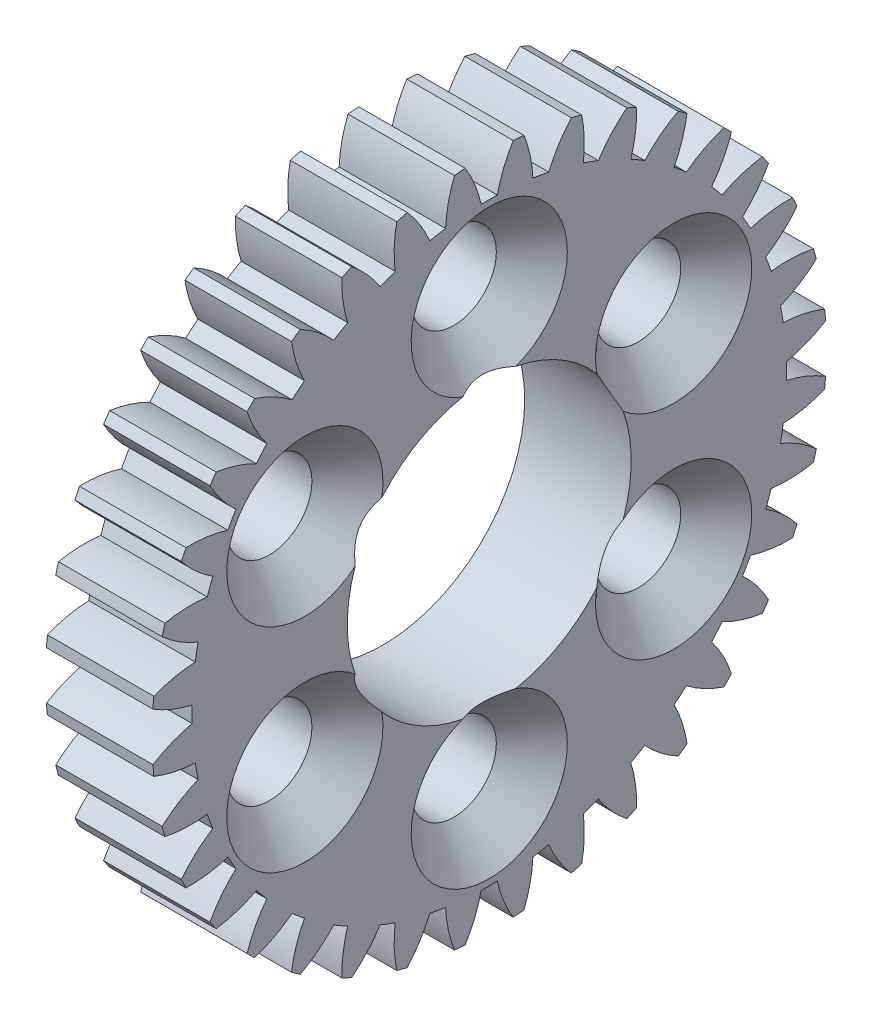
SolidWorks part; units mm, degrees
material "Náilon 101"
ref_plane "Plane1" through (0, 0, 0) normal (0, 0, 1) x (1, 0, 0)
ref_plane "Plane2" through (0, 0, 0) normal (0, 1, 0) x (1, 0, 0)
ref_plane "Plane3" through (0, 0, 0) normal (1, 0, 0) x (0, 0, -1)
sketch "HoldingSke" plane through (0, 0, 0) normal (0, 1, 0) x (1, 0, 0)
  line L0 (0, 0) -> (1.618, -1.1756)
  line L1 (-15, 0) -> (100, 0) construction
  line L2 (0, 0) -> (-2.1039, 2.3779)
  line L3 (0, 0) -> (-11.863, 4.5341)
  line L4 (0, 0) -> (6.9867, 5.0761)
  line L5 (0, 0) -> (-46.8476, -17.4728)
  line L6 (0, 0) -> (-2.4869, -1.6779)
  line L7 (-2.1039, 2.3779) -> (8.6586, 51.2059)
  line L8 (-76.2, 54.61) -> (-74.8, 54.61)
  line L9 (-71.009, 38.7566) -> (-53.1078, 45.2721)
  line L10 (-76.2, 71.12) -> (104.1128, 71.12)
  line L11 (0, 0) -> (-3, 0)
  line L12 (-76.2, 101.6) -> (-76.181, 101.6)
  line L13 (24.9733, 27.94) -> (52.9518, 28.4284)
  line L14 (24.9733, 27.94) -> (24.9743, 27.94)
  line L15 (24.9733, 27.94) -> (100.4006, 29.5858)
  line L16 (-63.627, -0.5) -> (-12.827, -0.5)
  circle A0 centre (0, 0) radius 4
  circle A1 centre (0, 0) radius 8.374
  circle A2 centre (0, 0) radius 37.5
  circle A3 centre (0, 0) radius 4
  dimension "MHD" = 16.748
  dimension "Hub_dia" = 75
  dimension "Bore" = 8
  dimension "MBD" = 8
  dimension "Num_teeth" = 36
  dimension "Pitch" = 2
  dimension "Overall_len" = 50
  dimension "Show_teeth" = 36
  dimension "Thickness" = 3
  dimension "OAL" = 50.0001
  dimension "T_dim" = 1.4
  dimension "Ap" = 20
  dimension "H" = 19.05
  dimension "Pitch_radius" = 180.3128
  dimension "Width" = 3
  dimension "Backlash" = 0.019
  dimension "Addendum_fac" = 1
  dimension "Dedendum_fac" = 1.25
  dimension "Clearance_fac" = 0.25
  dimension "Dedendum_add" = 0.001
  dimension "Module" = 0.5
sketch "BasProSke" plane through (0, 0, 0) normal (0, 1, 0) x (1, 0, 0)
  line L0 (-10, 0) -> (60, 0) construction
  line L1 (0, 0) -> (0, 9.5)
  line L2 (0, 0) -> (3, 0)
  line L3 (3, 0) -> (3, 9.5)
  line L4 (3, 9.5) -> (0, 9.5)
  dimension "Thickness" = 3
  dimension "Diameter" = 19
revolve "Base-Revolve" add sketch "BasProSke" angle 360 about L0
sketch "TooCutSke" plane through (0, 0, 0) normal (1, 0, 0) x (0, 0, -1)
  line L1 (0, 0) -> (0, 107) construction
  line L2 (0, 0) -> (-0.4258, 8.9899) construction
  line L3 (0, 0) -> (-1.5676, 17.9172) construction
  line L4 (-0.4258, 8.9899) -> (-0.7838, 8.9586) construction
  arc A0 (0.2272, 8.3709) -> (-0.2272, 8.3709) centre (0, 0) ccw
  arc A1 (0.6921, 9.5002) -> (-0.6921, 9.5002) centre (0, 0) ccw
  circle A2 centre (0, 0) radius 9 construction
  circle A3 centre (0, 0) radius 8.4572 construction
  arc A4 (-0.2272, 8.3709) -> (-0.6921, 9.5002) centre (-3.7404, 7.5851) ccw
  arc A5 (0.6921, 9.5002) -> (0.2272, 8.3709) centre (3.7404, 7.5851) ccw
  dimension "Root_dia" = 16.748
  dimension "Overcut_dia" = 19.0508
  dimension "Pitch_dia" = 18
  dimension "Base_dia" = 16.9145
  dimension "Flank_rad" = 3.6
  dimension "Half_ang" = 5
  dimension "Half_CT" = 0.3593
extrude "ToothCut" cut sketch "TooCutSke" along normal through all
fillet "Breaks" [suppressed] radius 0.01
fillet "RootFillets" [suppressed] radius 0.126
pattern_circular "TeethCuts" count 36 every 10 about axis through (-10, 0, 0) along (1, 0, 0) of "ToothCut", "RootFillets", "Breaks"
sketch "HubNeaOneSke" plane through (0, 0, 0) normal (-1, 0, 0) x (0, 0, 1)
  circle A0 centre (0, 0) radius 8.374
  dimension "Diameter" = 16.748
extrude "HubNearOne" [suppressed] add sketch "HubNeaOneSke" along normal blind 47.0001
sketch "HubNeaBotSke" plane through (0, 0, 0) normal (-1, 0, 0) x (0, 0, 1)
  circle A0 centre (0, 0) radius 8.374
  dimension "Diameter" = 16.748
extrude "HubNearBoth" [suppressed] add sketch "HubNeaBotSke" along normal blind 23.5
ref_plane "FarPln" through (3, 0, 0) normal (1, 0, 0) x (0, 0, -1)
sketch "HubFarSke" plane through (3, 0, 0) normal (1, 0, 0) x (0, 0, -1)
  circle A0 centre (0, 0) radius 8.374
  dimension "Diameter" = 16.748
extrude "HubFar" [suppressed] add sketch "HubFarSke" along normal blind 23.5
sketch "BorSke" plane through (0, 0, 0) normal (1, 0, 0) x (0, 0, -1)
  circle A0 centre (0, 0) radius 4
  dimension "Diameter" = 8
extrude "Bore" cut sketch "BorSke" along normal mid plane 100.0001
sketch "KeySke" plane through (0, 0, 0) normal (1, 0, 0) x (0, 0, -1)
  line L0 (-1.5, 0) -> (-1.5, 5.4)
  line L1 (-1.5, 5.4) -> (1.5, 5.4)
  line L2 (1.5, 5.4) -> (1.5, 0)
  line L3 (0, 0) -> (0, 34) construction
  line L4 (-1.5, 0) -> (1.5, 0)
  dimension "Width" = 3
  dimension "Offset" = 5.4
extrude "Keyway" [suppressed] cut sketch "KeySke" along normal mid plane 100.0001
pattern_circular "Keyway2" [suppressed] count 2 every 90 about axis through (-10, 0, 0) along (1, 0, 0)
sketch "Esboço1" plane through (3, 0, 0) normal (1, 0, 0) x (0, 0, -1)
  circle A0 centre (0, 0) radius 6 construction
  point P3 (0, 6)
  dimension "D1" = 12
hole_wizard "Escareado para parafuso com cabeça escareada chata de M21" positions "3DSketch2" profile "Esboço2" countersink size "M2" standard "ISO"
sketch3d "3DSketch2"
  point P0 (3, 6, 0)
sketch "Esboço2" plane through (3, 6, 0) normal (0, 1, 0) x (0, 0, -1)
  line L0 (0, 0) -> (0, 3.721)
  line L1 (0, 3.721) -> (1.2, 3)
  line L2 (1.2, 3) -> (1.2, 1)
  line L3 (1.2, 1) -> (2.2, 0)
  line L5 (2.2, 0) -> (0, 0)
  line L6 (-1.2, 1) -> (-2.2, 0) construction
  line L10 (0, 3.721) -> (-1.2, 3) construction
  line L11 (0, -6.35) -> (0, 107.95) construction
  dimension "Hole Dia." = 2.4
  dimension "Hole Depth" = 3
  dimension "Near C'Sink Dia." = 4.4
  dimension "Near C'Sink Angle" = 90
  dimension "Drill Angle" = 118
pattern_circular "PadrãoCircular1" count 6 over 360 about axis through (0, 0, 0) along (1, 0, 0) of "Escareado para parafuso com cabeça escareada chata de M21"
sketch "Esboço3" plane through (3, 0, 0) normal (1, 0, 0) x (0, 0, -1)
  line L0 (0, 0) -> (4, 0) construction
  line L1 (0, 0) -> (-4, 0) construction
  arc A0 (-3.031, -2.6102) -> (-0.7451, -3.93) centre (0, 0) ccw construction
  arc A1 (-0.7451, 3.93) -> (-3.031, 2.6102) centre (0, 0) ccw construction
equation "' \"Module@HoldingSke\" = 6.35"
equation "' \"Num_teeth@HoldingSke\" = 12"
equation "' \"Ap@HoldingSke\" =  20"
equation "' \"Ap@HoldingSke\" = 20"
equation "' \"Width@HoldingSke\" = 0.5 * 25.4"
equation "' \"Hub_dia@HoldingSke\"= 1 * 25.4"
equation "' \"Hub_dia@HoldingSke\" = 1 * 25.4"
equation "' \"Overall_len@HoldingSke\" = 1.0 * 25.4"
equation "' \"Bore@HoldingSke\" = 0.75 * 25.4"
equation "' \"T_dim@HoldingSke\" = 0.1 * 25.4"
equation "' \"Width@KeySke\" = 0.25 * 25.4"
equation "' \"Show_teeth@HoldingSke\" = 13"
equation "' \"Backlash@HoldingSke\" = 0.009 * 25.4"
equation "' \"Addendum_fac@HoldingSke\" = 1.0"
equation "' \"Dedendum_fac@HoldingSke\" = 1.25"
equation "' \"Dedendum_add@HoldingSke\" = 0.00005 * 25.4"
equation "' \"Clearance_fac@HoldingSke\" = 0.25"
equation "\"Pitch@HoldingSke\" = 1 / \"Module@HoldingSke\""
equation "\"Overcut_dia@TooCutSke\" = (\"Num_teeth@HoldingSke\" + 2 * \"Addendum_fac@HoldingSke\") / \"Pitch@HoldingSke\" + 0.002 * 25.4"
equation "\"Pitch_dia@TooCutSke\" = \"Num_teeth@HoldingSke\" / \"Pitch@HoldingSke\""
equation "\"Base_dia@TooCutSke\" = \"Num_teeth@HoldingSke\" / \"Pitch@HoldingSke\" * cos((\"Ap@HoldingSke\"  * 3.14159265 / 180))"
equation "\"Root_dia@TooCutSke\" = (\"Num_teeth@HoldingSke\" + 2) / \"Pitch@HoldingSke\" - 2 * (\"Addendum_fac@HoldingSke\" + \"Dedendum_fac@HoldingSke\") / \"Pitch@HoldingSke\" - \"Dedendum_add@HoldingSke\" * 2"
equation "\"Half_ang@TooCutSke\" = 180 / \"Num_teeth@HoldingSke\""
equation "\"Half_CT@TooCutSke\" = \"Num_teeth@HoldingSke\" / \"Pitch@HoldingSke\" * sin((3.14159265 / 2 / \"Num_teeth@HoldingSke\")) / 2 - 7 * \"Backlash@HoldingSke\" / 4"
equation "\"Flank_rad@TooCutSke\" = \"Num_teeth@HoldingSke\" / \"Pitch@HoldingSke\" / 5"
equation "\"Radius@RootFillets\" = \"Clearance_fac@HoldingSke\" / \"Pitch@HoldingSke\" + \"Dedendum_add@HoldingSke\""
equation "\"Break_rad@Breaks\" = 0.02 / \"Pitch@HoldingSke\""
equation "\"Thickness@HoldingSke\" = \"Width@HoldingSke\""
equation "\"OAL@HoldingSke\" = \"Thickness@HoldingSke\""
equation "\"MHD@HoldingSke\" = (\"Num_teeth@HoldingSke\" + 2) / \"Pitch@HoldingSke\" - 2 * (\"Addendum_fac@HoldingSke\" + \"Dedendum_fac@HoldingSke\")  / \"Pitch@HoldingSke\" - \"Dedendum_add@HoldingSke\" * 2"
equation "\"MBD@HoldingSke\" = (\"Num_teeth@HoldingSke\" + 2) / \"Pitch@HoldingSke\" - 2 * (\"Addendum_fac@HoldingSke\" + \"Dedendum_fac@HoldingSke\")  / \"Pitch@HoldingSke\" - \"Dedendum_add@HoldingSke\" * 2 - 0.002 * 25.4"
equation "\"MHD@HoldingSke\" = ((sgn( \"MHD@HoldingSke\" - \"Hub_dia@HoldingSke\" )-1)*( \"MHD@HoldingSke\" - \"Hub_dia@HoldingSke\" ))/-2+ \"Hub_dia@HoldingSke\""
equation "\"MBD@HoldingSke\" = ((sgn( \"MBD@HoldingSke\" - \"Bore@HoldingSke\" )-1)*( \"MBD@HoldingSke\" - \"Bore@HoldingSke\" ))/-2+ \"Bore@HoldingSke\""
equation "\"OAL@HoldingSke\" = ((sgn( \"OAL@HoldingSke\" - \"Overall_len@HoldingSke\" )+1)*( \"OAL@HoldingSke\" - \"Overall_len@HoldingSke\" ))/2 + \"Overall_len@HoldingSke\" + 0.000002 * 25.4"
equation "\"Num_teeth@TeethCuts\" = int( \"Show_teeth@HoldingSke\" ) + 1"
equation "\"Num_teeth@TeethCuts\" = ((sgn( \"Num_teeth@TeethCuts\" - \"Num_teeth@HoldingSke\" )-1)*( \"Num_teeth@TeethCuts\" - \"Num_teeth@HoldingSke\" ))/-2+ \"Num_teeth@HoldingSke\""
equation "\"Num_teeth@TeethCuts\" = ((sgn( \"Num_teeth@TeethCuts\" - 2.0)+1)*( \"Num_teeth@TeethCuts\" - 2.0))/2 +2.0"
equation "\"Angle@TeethCuts\" = 360.0 / \"Num_teeth@HoldingSke\""
equation "\"Diameter@BasProSke\" = (\"Num_teeth@HoldingSke\" + 2 * \"Addendum_fac@HoldingSke\") / \"Pitch@HoldingSke\""
equation "\"Thickness@BasProSke\"  = \"Thickness@HoldingSke\""
equation "' \"Fillet_rad@BasProSke\" =  \"Thickness@HoldingSke\" * 0.05"
equation "' \"Fillet_rad@BasProSke\" = \"Thickness@HoldingSke\" * 0.05"
equation "\"MHD@HoldingSke\" = ((sgn( \"MHD@HoldingSke\" - \"Root_dia@TooCutSke\" )-1)*( \"MHD@HoldingSke\" - \"Root_dia@TooCutSke\" ))/-2+ \"Root_dia@TooCutSke\""
equation "\"Diameter@HubNeaOneSke\" = \"MHD@HoldingSke\""
equation "\"Length@HubNearOne\" = \"OAL@HoldingSke\" - \"Thickness@BasProSke\""
equation "\"Diameter@HubNeaBotSke\" = \"MHD@HoldingSke\""
equation "\"Length@HubNearBoth\" = ( \"OAL@HoldingSke\" - \"Thickness@BasProSke\" ) / 2.0"
equation "\"Thickness@FarPln\" = \"Thickness@BasProSke\""
equation "\"Diameter@HubFarSke\" = \"MHD@HoldingSke\""
equation "\"Length@HubFar\" = ( \"OAL@HoldingSke\" - \"Thickness@BasProSke\" ) / 2.0"
equation "\"Diameter@BorSke\" = \"MBD@HoldingSke\""
equation "\"D1@Bore\" = \"OAL@HoldingSke\" * 2.0"
equation "\"D1@Keyway\" = \"OAL@HoldingSke\" * 2.0"
equation "\"Offset@KeySke\" = \"T_dim@HoldingSke\" + \"MBD@HoldingSke\" / 2.0"
